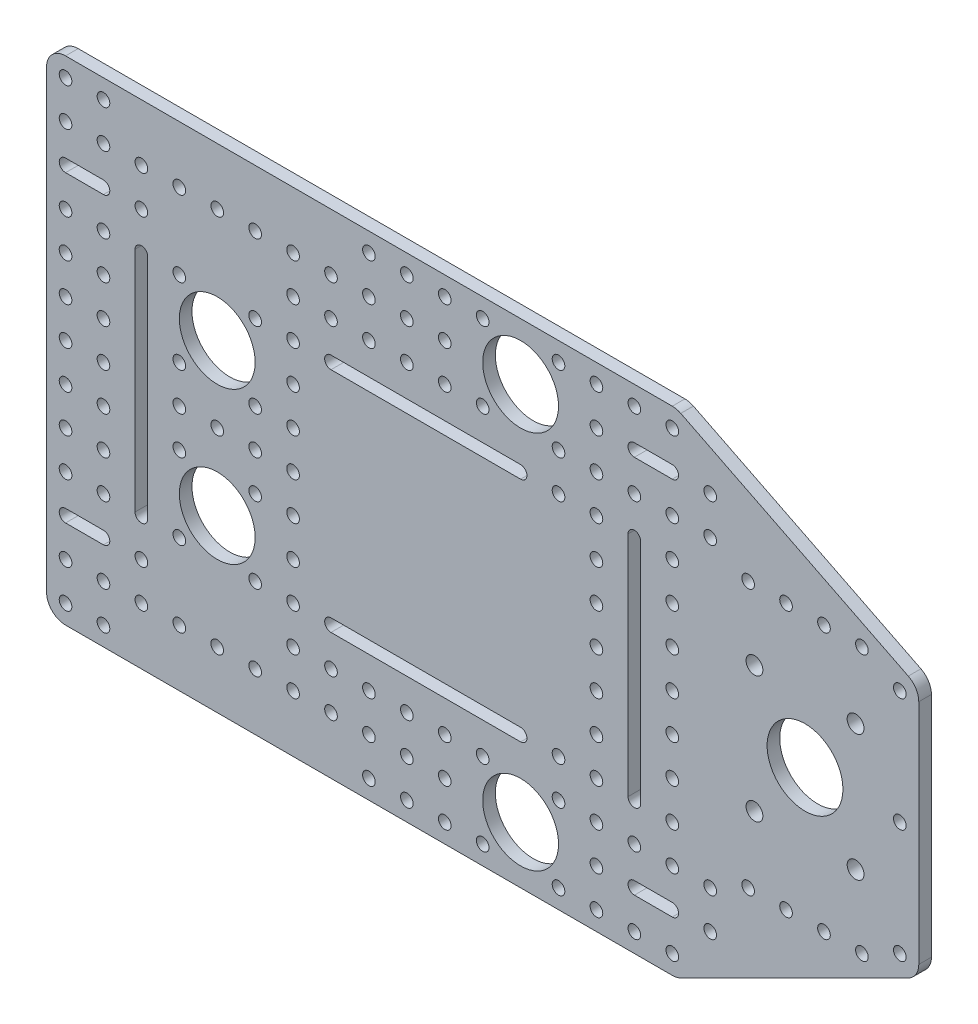
SolidWorks part; units mm, degrees
ref_plane "Alzado" through (0, 0, 0) normal (0, 0, 1) x (1, 0, 0)
ref_plane "Planta" through (0, 0, 0) normal (0, 1, 0) x (1, 0, 0)
ref_plane "Vista lateral" through (0, 0, 0) normal (1, 0, 0) x (0, 0, -1)
sketch "Model" plane through (0, 0, 0) normal (0, 0, 1) x (1, 0, 0)
  line L0 (391.4291, 507.7422) -> (535.4291, 507.7422)
  line L1 (593.9291, 476.2422) -> (593.9291, 422.2422)
  line L2 (386.9291, 503.2422) -> (386.9291, 395.2422)
  line L3 (537.4416, 507.2672) -> (591.4416, 480.2672)
  line L4 (591.4416, 418.2173) -> (537.4416, 391.2173)
  line L5 (391.4291, 390.7422) -> (535.4291, 390.7422)
  line L6 (407.9291, 476.2422) -> (407.9291, 422.2422)
  line L7 (410.9291, 422.2422) -> (410.9291, 476.2422)
  line L8 (524.9291, 476.2422) -> (524.9291, 422.2422)
  line L9 (527.9291, 422.2422) -> (527.9291, 476.2422)
  line L10 (526.4291, 495.7422) -> (535.4291, 495.7422)
  line L11 (535.4291, 492.7422) -> (526.4291, 492.7422)
  line L12 (526.4291, 405.7422) -> (535.4291, 405.7422)
  line L13 (535.4291, 402.7422) -> (526.4291, 402.7422)
  line L14 (391.4291, 486.7422) -> (400.4291, 486.7422)
  line L15 (400.4291, 483.7422) -> (391.4291, 483.7422)
  line L16 (400.4291, 414.7422) -> (391.4291, 414.7422)
  line L17 (391.4291, 411.7422) -> (400.4291, 411.7422)
  line L18 (454.4291, 474.7422) -> (499.4291, 474.7422)
  line L19 (499.4291, 477.7422) -> (454.4291, 477.7422)
  line L20 (454.4291, 420.7422) -> (499.4291, 420.7422)
  line L21 (499.4291, 423.7422) -> (454.4291, 423.7422)
  circle A0 centre (391.4291, 476.2422) radius 1.5
  circle A1 centre (391.4291, 467.2422) radius 1.5
  circle A2 centre (391.4291, 458.2422) radius 1.5
  circle A3 centre (391.4291, 449.2422) radius 1.5
  circle A4 centre (391.4291, 440.2422) radius 1.5
  circle A5 centre (391.4291, 431.2422) radius 1.5
  circle A6 centre (391.4291, 422.2422) radius 1.5
  circle A7 centre (391.4291, 404.2422) radius 1.5
  circle A8 centre (391.4291, 395.2422) radius 1.5
  circle A9 centre (400.4291, 476.2422) radius 1.5
  circle A10 centre (400.4291, 467.2422) radius 1.5
  circle A11 centre (400.4291, 458.2422) radius 1.5
  circle A12 centre (400.4291, 449.2422) radius 1.5
  circle A13 centre (400.4291, 440.2422) radius 1.5
  circle A14 centre (400.4291, 431.2422) radius 1.5
  circle A15 centre (400.4291, 422.2422) radius 1.5
  circle A16 centre (400.4291, 404.2422) radius 1.5
  circle A17 centre (400.4291, 395.2422) radius 1.5
  circle A18 centre (409.4291, 413.2422) radius 1.5
  circle A19 centre (409.4291, 404.2422) radius 1.5
  circle A20 centre (418.4291, 476.2422) radius 1.5
  circle A21 centre (418.4291, 458.2422) radius 1.5
  circle A22 centre (418.4291, 449.2422) radius 1.5
  circle A23 centre (418.4291, 440.2422) radius 1.5
  circle A24 centre (418.4291, 422.2422) radius 1.5
  circle A25 centre (418.4291, 404.2422) radius 1.5
  circle A26 centre (427.4291, 449.2422) radius 1.5
  circle A27 centre (427.4291, 404.2422) radius 1.5
  circle A28 centre (436.4291, 476.2422) radius 1.5
  circle A29 centre (436.4291, 458.2422) radius 1.5
  circle A30 centre (436.4291, 449.2422) radius 1.5
  circle A31 centre (436.4291, 440.2422) radius 1.5
  circle A32 centre (436.4291, 422.2422) radius 1.5
  circle A33 centre (436.4291, 404.2422) radius 1.5
  circle A34 centre (445.4291, 476.2422) radius 1.5
  circle A35 centre (445.4291, 467.2422) radius 1.5
  circle A36 centre (445.4291, 458.2422) radius 1.5
  circle A37 centre (445.4291, 449.2422) radius 1.5
  circle A38 centre (445.4291, 440.2422) radius 1.5
  circle A39 centre (445.4291, 431.2422) radius 1.5
  circle A40 centre (445.4291, 422.2422) radius 1.5
  circle A41 centre (445.4291, 413.2422) radius 1.5
  circle A42 centre (445.4291, 404.2422) radius 1.5
  circle A43 centre (454.4291, 413.2422) radius 1.5
  circle A44 centre (454.4291, 404.2422) radius 1.5
  circle A45 centre (463.4291, 413.2422) radius 1.5
  circle A46 centre (463.4291, 404.2422) radius 1.5
  circle A47 centre (463.4291, 395.2422) radius 1.5
  circle A48 centre (472.4291, 413.2422) radius 1.5
  circle A49 centre (472.4291, 404.2422) radius 1.5
  circle A50 centre (472.4291, 395.2422) radius 1.5
  circle A51 centre (481.4291, 413.2422) radius 1.5
  circle A52 centre (481.4291, 404.2422) radius 1.5
  circle A53 centre (481.4291, 395.2422) radius 1.5
  circle A54 centre (490.4291, 413.2422) radius 1.5
  circle A55 centre (490.4291, 395.2422) radius 1.5
  circle A56 centre (508.4291, 413.2422) radius 1.5
  circle A57 centre (508.4291, 395.2422) radius 1.5
  arc A58 (391.4291, 507.7422) -> (386.9291, 503.2422) centre (391.4291, 503.2422) ccw
  arc A59 (386.9291, 395.2422) -> (391.4291, 390.7422) centre (391.4291, 395.2422) ccw
  circle A60 centre (544.4291, 413.2422) radius 1.5
  circle A61 centre (544.4291, 404.2422) radius 1.5
  circle A62 centre (553.4291, 417.7422) radius 1.5
  circle A63 centre (562.4291, 417.7422) radius 1.5
  circle A64 centre (571.4291, 417.7422) radius 1.5
  circle A65 centre (580.4291, 417.7422) radius 1.5
  circle A66 centre (589.4291, 476.2422) radius 1.5
  circle A67 centre (589.4291, 449.2422) radius 1.5
  circle A68 centre (589.4291, 422.2422) radius 1.5
  circle A69 centre (535.4291, 476.2422) radius 1.5
  circle A70 centre (535.4291, 467.2422) radius 1.5
  circle A71 centre (535.4291, 458.2422) radius 1.5
  circle A72 centre (535.4291, 449.2422) radius 1.5
  circle A73 centre (535.4291, 440.2422) radius 1.5
  circle A74 centre (535.4291, 431.2422) radius 1.5
  circle A75 centre (535.4291, 422.2422) radius 1.5
  circle A76 centre (535.4291, 413.2422) radius 1.5
  circle A77 centre (535.4291, 395.2422) radius 1.5
  circle A78 centre (391.4291, 503.2422) radius 1.5
  circle A79 centre (400.4291, 503.2422) radius 1.5
  circle A80 centre (409.4291, 485.2422) radius 1.5
  circle A81 centre (454.4291, 485.2422) radius 1.5
  circle A82 centre (463.4291, 503.2422) radius 1.5
  circle A83 centre (463.4291, 485.2422) radius 1.5
  circle A84 centre (472.4291, 503.2422) radius 1.5
  circle A85 centre (472.4291, 485.2422) radius 1.5
  circle A86 centre (481.4291, 503.2422) radius 1.5
  circle A87 centre (481.4291, 485.2422) radius 1.5
  circle A88 centre (490.4291, 503.2422) radius 1.5
  circle A89 centre (490.4291, 485.2422) radius 1.5
  circle A90 centre (508.4291, 503.2422) radius 1.5
  circle A91 centre (508.4291, 485.2422) radius 1.5
  circle A92 centre (544.4291, 485.2422) radius 1.5
  circle A93 centre (553.4291, 480.7422) radius 1.5
  circle A94 centre (562.4291, 480.7422) radius 1.5
  circle A95 centre (571.4291, 480.7422) radius 1.5
  circle A96 centre (580.4291, 480.7422) radius 1.5
  circle A97 centre (535.4291, 503.2422) radius 1.5
  circle A98 centre (535.4291, 485.2422) radius 1.5
  circle A99 centre (391.4291, 494.2422) radius 1.5
  circle A100 centre (400.4291, 494.2422) radius 1.5
  circle A101 centre (409.4291, 494.2422) radius 1.5
  circle A102 centre (418.4291, 494.2422) radius 1.5
  circle A103 centre (427.4291, 494.2422) radius 1.5
  circle A104 centre (436.4291, 494.2422) radius 1.5
  circle A105 centre (445.4291, 494.2422) radius 1.5
  circle A106 centre (454.4291, 494.2422) radius 1.5
  circle A107 centre (463.4291, 494.2422) radius 1.5
  circle A108 centre (472.4291, 494.2422) radius 1.5
  circle A109 centre (481.4291, 494.2422) radius 1.5
  circle A110 centre (544.4291, 494.2422) radius 1.5
  circle A111 centre (427.4291, 467.2422) radius 9
  circle A112 centre (427.4291, 431.2422) radius 9
  circle A113 centre (508.4291, 476.2422) radius 1.5
  circle A114 centre (508.4291, 422.2422) radius 1.5
  arc A115 (535.4291, 390.7422) -> (537.4416, 391.2173) centre (535.4291, 395.2422) ccw
  arc A116 (537.4416, 507.2672) -> (535.4291, 507.7422) centre (535.4291, 503.2422) ccw
  arc A117 (593.9291, 476.2422) -> (591.4416, 480.2672) centre (589.4291, 476.2422) ccw
  arc A118 (591.4416, 418.2173) -> (593.9291, 422.2422) centre (589.4291, 422.2422) ccw
  circle A119 centre (517.4291, 476.2422) radius 1.5
  circle A120 centre (517.4291, 467.2422) radius 1.5
  circle A121 centre (517.4291, 458.2422) radius 1.5
  circle A122 centre (517.4291, 449.2422) radius 1.5
  circle A123 centre (517.4291, 440.2422) radius 1.5
  circle A124 centre (517.4291, 431.2422) radius 1.5
  circle A125 centre (517.4291, 422.2422) radius 1.5
  circle A126 centre (517.4291, 413.2422) radius 1.5
  circle A127 centre (517.4291, 404.2422) radius 1.5
  circle A128 centre (517.4291, 395.2422) radius 1.5
  circle A129 centre (526.4291, 413.2422) radius 1.5
  circle A130 centre (526.4291, 395.2422) radius 1.5
  circle A131 centre (517.4291, 503.2422) radius 1.5
  circle A132 centre (517.4291, 485.2422) radius 1.5
  circle A133 centre (526.4291, 503.2422) radius 1.5
  circle A134 centre (526.4291, 485.2422) radius 1.5
  circle A135 centre (517.4291, 494.2422) radius 1.5
  arc A136 (410.9291, 476.2422) -> (407.9291, 476.2422) centre (409.4291, 476.2422) ccw
  arc A137 (407.9291, 422.2422) -> (410.9291, 422.2422) centre (409.4291, 422.2422) ccw
  circle A138 centre (445.4291, 485.2422) radius 1.5
  arc A139 (527.9291, 476.2422) -> (524.9291, 476.2422) centre (526.4291, 476.2422) ccw
  arc A140 (524.9291, 422.2422) -> (527.9291, 422.2422) centre (526.4291, 422.2422) ccw
  circle A141 centre (499.4291, 494.2422) radius 9
  circle A142 centre (499.4291, 404.2422) radius 9
  arc A143 (526.4291, 495.7422) -> (526.4291, 492.7422) centre (526.4291, 494.2422) ccw
  arc A144 (535.4291, 492.7422) -> (535.4291, 495.7422) centre (535.4291, 494.2422) ccw
  arc A145 (526.4291, 405.7422) -> (526.4291, 402.7422) centre (526.4291, 404.2422) ccw
  arc A146 (535.4291, 402.7422) -> (535.4291, 405.7422) centre (535.4291, 404.2422) ccw
  arc A147 (391.4291, 414.7422) -> (391.4291, 411.7422) centre (391.4291, 413.2422) ccw
  arc A148 (400.4291, 411.7422) -> (400.4291, 414.7422) centre (400.4291, 413.2422) ccw
  arc A149 (391.4291, 486.7422) -> (391.4291, 483.7422) centre (391.4291, 485.2422) ccw
  arc A150 (400.4291, 483.7422) -> (400.4291, 486.7422) centre (400.4291, 485.2422) ccw
  arc A151 (454.4291, 477.7422) -> (454.4291, 474.7422) centre (454.4291, 476.2422) ccw
  arc A152 (499.4291, 474.7422) -> (499.4291, 477.7422) centre (499.4291, 476.2422) ccw
  arc A153 (454.4291, 423.7422) -> (454.4291, 420.7422) centre (454.4291, 422.2422) ccw
  arc A154 (499.4291, 420.7422) -> (499.4291, 423.7422) centre (499.4291, 422.2422) ccw
  circle A155 centre (578.9291, 434.2422) radius 2
  circle A156 centre (578.9291, 464.2422) radius 2
  circle A157 centre (554.9291, 464.2422) radius 2
  circle A158 centre (554.9291, 434.2422) radius 2
  circle A159 centre (566.9291, 449.2422) radius 9
extrude "Saliente-Extruir1" add sketch "Model" along normal blind 3
